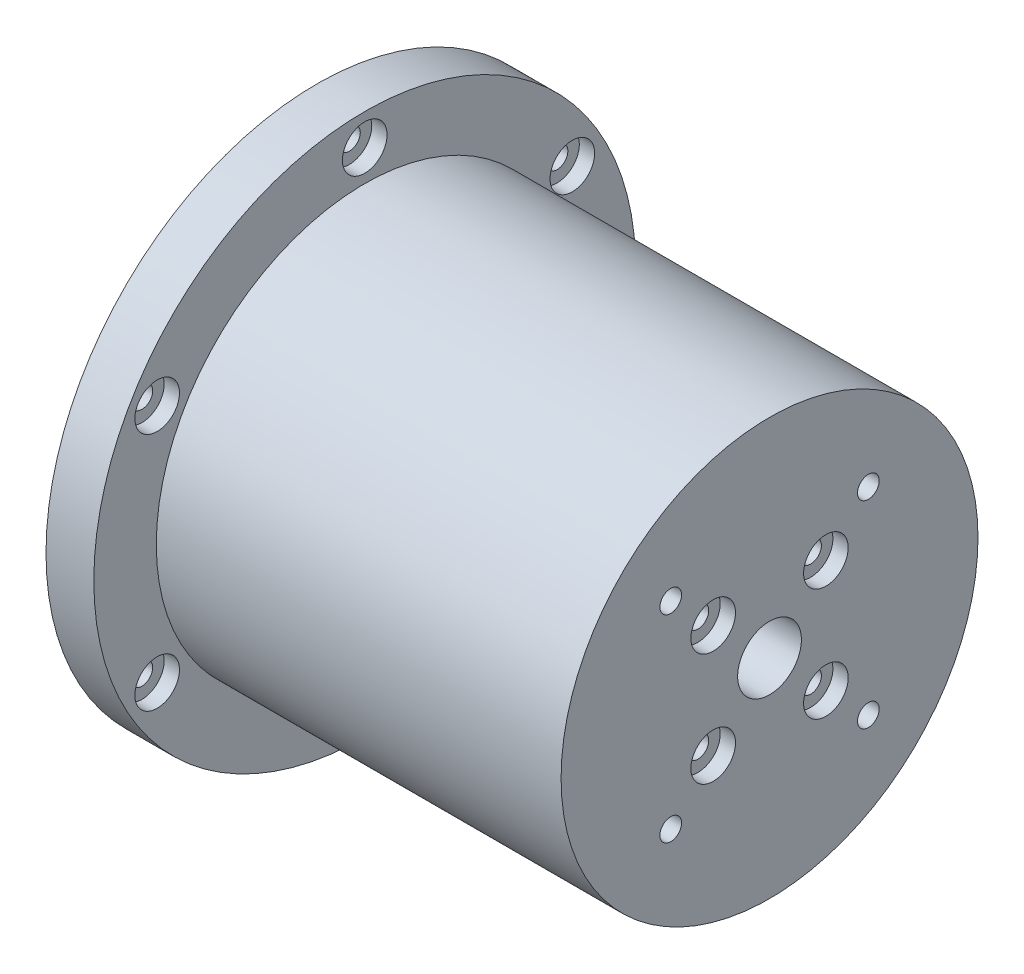
SolidWorks part; units mm, degrees
material "6063-T5"
ref_plane "Front" through (0, 0, 0) normal (0, 0, 1) x (1, 0, 0)
ref_plane "Top" through (0, 0, 0) normal (0, 1, 0) x (1, 0, 0)
ref_plane "Right" through (0, 0, 0) normal (1, 0, 0) x (0, 0, -1)
sketch "Croquis1" plane through (0, 0, 0) normal (1, 0, 0) x (0, 0, -1)
  circle A0 centre (0, 0) radius 32.7
  circle A1 centre (0, 0) radius 5
  dimension "D1" = 65.4
  dimension "D2" = 10
extrude "Saliente-Extruir1" add sketch "Croquis1" along normal mid plane 8.5
hole_wizard "Refrentado para tornillo con cabeza troncocónica de M31" positions "Croquis2" profile "Croquis4" counterbore size "M3" standard "Ansi Metric" end condition up to next
sketch "Croquis2" plane through (4.25, 0, 0) normal (1, 0, 0) x (0, 0, -1)
  line L1 (-8.8388, -8.8388) -> (8.8388, -8.8388) construction
  line L2 (-8.8388, -8.8388) -> (-8.8388, 8.8388) construction
  line L3 (-8.8388, 8.8388) -> (8.8388, 8.8388) construction
  line L4 (8.8388, -8.8388) -> (8.8388, 8.8388) construction
  line L5 (-8.8388, -8.8388) -> (8.8388, 8.8388) construction
  line L6 (-8.8388, 8.8388) -> (8.8388, -8.8388) construction
  point P2 (8.8388, 8.8388)
  point P25 (-8.8388, -8.8388)
  point P26 (-8.8388, 8.8388)
  point P27 (8.8388, -8.8388)
  dimension "D1" = 25
sketch "Croquis4" plane through (4.25, 8.8388, -8.8388) normal (0, 1, 0) x (0, 0, -1)
  line L0 (0, 0) -> (0, 8.5)
  line L1 (0, 8.5) -> (1.7, 8.5)
  line L3 (1.7, 8.5) -> (1.7, 2.4)
  line L4 (1.7, 2.4) -> (3.5, 2.4)
  line L5 (3.5, 2.4) -> (3.5, 0)
  line L7 (3.5, 0) -> (0, 0)
  line L11 (0, -6.35) -> (0, 107.95) construction
  dimension "Diámetro de taladro hasta el siguiente" = 3.4
  dimension "Profundidad de taladro hasta el siguiente" = 8.5
  dimension "Diámetro de refrentado" = 7
  dimension "Profundidad de refrentado" = 2.4
sketch "Croquis5" plane through (-4.25, 0, 0) normal (-1, 0, 0) x (0, 0, 1)
  circle A0 centre (0, 0) radius 21.5
  circle A1 centre (0, 0) radius 32.7 construction
  circle A2 centre (0, 0) radius 32.7
  dimension "D1" = 43
extrude "Saliente-Extruir2" add sketch "Croquis5" along normal blind 55
hole_wizard "Taladro de margen para M31" positions "Croquis6" profile "Croquis8" hole size "M3" standard "Ansi Metric"
sketch "Croquis6" plane through (-59.25, 0, 0) normal (-1, 0, 0) x (0, 0, 1)
  line L1 (-17.075, -17.075) -> (17.075, -17.075) construction
  line L2 (-17.075, -17.075) -> (-17.075, 17.075) construction
  line L3 (-17.075, 17.075) -> (17.075, 17.075) construction
  line L4 (17.075, -17.075) -> (17.075, 17.075) construction
  line L5 (-17.075, -17.075) -> (17.075, 17.075) construction
  line L6 (-17.075, 17.075) -> (17.075, -17.075) construction
  point P2 (17.075, 17.075)
  point P25 (-17.075, -17.075)
  point P26 (-17.075, 17.075)
  point P27 (17.075, -17.075)
  dimension "D1" = 34.15
sketch "Croquis8" plane through (-59.25, 17.075, 17.075) normal (0, 1, 0) x (0, 0, 1)
  line L0 (0, 0) -> (0, 16.0215)
  line L1 (0, 16.0215) -> (1.7, 15)
  line L2 (1.7, 15) -> (1.7, 0)
  line L5 (1.7, 0) -> (0, 0)
  line L10 (0, 16.0215) -> (-1.7, 15) construction
  line L11 (0, -6.35) -> (0, 107.95) construction
  dimension "Diámetro de taladro" = 3.4
  dimension "Profundidad de taladro" = 15
  dimension "Ángulo de perforador" = 118
hole_wizard "Taladro de margen para M32" positions "Croquis9" profile "Croquis10" hole size "M3" standard "Ansi Metric"
sketch "Croquis9" plane through (4.25, 0, 0) normal (1, 0, 0) x (0, 0, -1)
  line L1 (-15.5, -15.5) -> (15.5, -15.5) construction
  line L2 (-15.5, -15.5) -> (-15.5, 15.5) construction
  line L3 (-15.5, 15.5) -> (15.5, 15.5) construction
  line L4 (15.5, -15.5) -> (15.5, 15.5) construction
  line L5 (-15.5, -15.5) -> (15.5, 15.5) construction
  line L6 (-15.5, 15.5) -> (15.5, -15.5) construction
  point P2 (15.5, 15.5)
  point P13 (-15.5, -15.5)
  point P14 (-15.5, 15.5)
  point P15 (15.5, -15.5)
  dimension "D1" = 31
sketch "Croquis10" plane through (4.25, 15.5, -15.5) normal (0, 1, 0) x (0, 0, -1)
  line L0 (0, 0) -> (0, 17.5215)
  line L1 (0, 17.5215) -> (1.7, 16.5)
  line L2 (1.7, 16.5) -> (1.7, 0)
  line L5 (1.7, 0) -> (0, 0)
  line L10 (0, 17.5215) -> (-1.7, 16.5) construction
  line L11 (0, -6.35) -> (0, 107.95) construction
  dimension "Diámetro de taladro" = 3.4
  dimension "Profundidad de taladro" = 16.5
  dimension "Ángulo de perforador" = 118
sketch "Croquis16" plane through (-59.25, 0, 0) normal (-1, 0, 0) x (0, 0, 1)
  line L6 (-18.5, -21.5) -> (18.5, -21.5)
  line L14 (-21.5, -18.5) -> (-21.5, 18.5)
  line L15 (-18.5, 21.5) -> (18.5, 21.5)
  line L16 (21.5, -18.5) -> (21.5, 18.5)
  line L17 (-21.5, -21.5) -> (21.5, 21.5) construction
  line L18 (-21.5, 21.5) -> (21.5, -21.5) construction
  circle A1 centre (0, 0) radius 42.5
  circle A3 centre (0, 0) radius 21.5 construction
  arc A4 (-18.5, -21.5) -> (-21.5, -18.5) centre (-18.5, -18.5) cw
  arc A5 (18.5, -21.5) -> (21.5, -18.5) centre (18.5, -18.5) ccw
  arc A6 (18.5, 21.5) -> (21.5, 18.5) centre (18.5, 18.5) cw
  arc A7 (-21.5, 18.5) -> (-18.5, 21.5) centre (-18.5, 18.5) cw
  dimension "D1" = 85
  dimension "D2" = 3
extrude "Saliente-Extruir3" add sketch "Croquis16" along normal blind 7.5
hole_wizard "Refrentado para tornillo con cabeza troncocónica de M32" positions "Croquis20" profile "Croquis21" counterbore size "M3" standard "Ansi Metric" end condition up to next
sketch "Croquis20" plane through (-59.25, 0, 0) normal (1, 0, 0) x (0, 0, -1)
  line L0 (0, 42.5) -> (0, 32.7) construction
  line L1 (0, 34.925) -> (0, -34.925) construction
  circle A0 centre (0, 0) radius 42.5 construction
  circle A1 centre (0, 0) radius 32.7 construction
  point P14 (0, 37.6)
  point P21 (32.5626, 18.8)
  point P22 (32.5626, -18.8)
  point P23 (0, -37.6)
  point P24 (-32.5626, -18.8)
  point P25 (-32.5626, 18.8)
  dimension "D1" = 6
sketch "Croquis21" plane through (-59.25, 18.8, 32.5626) normal (0, 1, 0) x (0, 0, -1)
  line L0 (0, 0) -> (0, 7.5)
  line L1 (0, 7.5) -> (1.7, 7.5)
  line L3 (1.7, 7.5) -> (1.7, 2.4)
  line L4 (1.7, 2.4) -> (3.5, 2.4)
  line L5 (3.5, 2.4) -> (3.5, 0)
  line L7 (3.5, 0) -> (0, 0)
  line L11 (0, -6.35) -> (0, 107.95) construction
  dimension "Diámetro de taladro hasta el siguiente" = 3.4
  dimension "Profundidad de taladro hasta el siguiente" = 7.5
  dimension "Diámetro de refrentado" = 7
  dimension "Profundidad de refrentado" = 2.4
